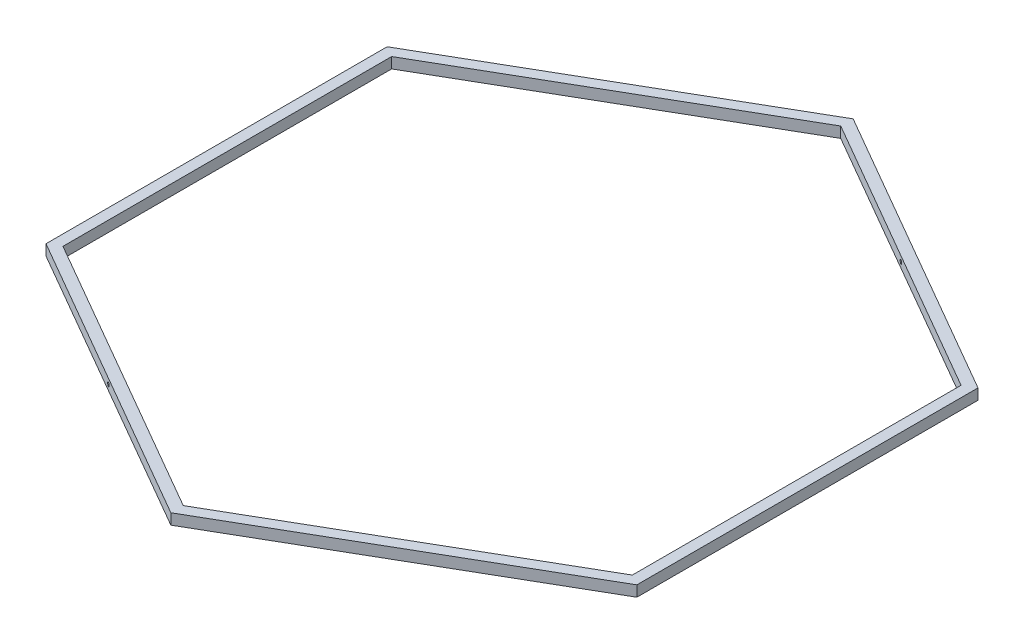
SolidWorks part; units mm, degrees
ref_plane "Plano frontal" through (0, 0, 0) normal (0, 0, 1) x (1, 0, 0)
ref_plane "Plano superior" through (0, 0, 0) normal (0, 1, 0) x (1, 0, 0)
ref_plane "Plano direito" through (0, 0, 0) normal (1, 0, 0) x (0, 0, -1)
sketch "Esboço1" plane through (0, 0, 0) normal (0, 1, 0) x (1, 0, 0)
  line L0 (110, -63.5085) -> (110, 63.5085)
  line L1 (110, 63.5085) -> (0, 127.0171)
  line L2 (0, 127.0171) -> (-110, 63.5085)
  line L3 (-110, 63.5085) -> (-110, -63.5085)
  line L4 (-110, -63.5085) -> (0, -127.0171)
  line L5 (0, -127.0171) -> (110, -63.5085)
  line L6 (106, 61.1991) -> (0, 122.3983)
  line L7 (0, 122.3983) -> (-106, 61.1991)
  line L8 (-106, 61.1991) -> (-106, -61.1991)
  line L9 (-106, -61.1991) -> (0, -122.3983)
  line L10 (0, -122.3983) -> (106, -61.1991)
  line L11 (106, -61.1991) -> (106, 61.1991)
  circle A0 centre (0, 0) radius 110 construction
  dimension "D1" = 220
  dimension "D2" = 4
extrude "Ressalto-extrusão1" add sketch "Esboço1" along normal blind 4
sketch "Esboço2" plane through (-55, 0, 95.2628) normal (-0.5, 0, 0.866) x (0.866, 0, 0.5)
  line L0 (-63.5085, 2) -> (0, 2) construction
  line L1 (-63.5085, 4) -> (-63.5085, 0) construction
  line L2 (0, 2) -> (63.5085, 2) construction
  line L3 (63.5085, 4) -> (63.5085, 0) construction
  circle A0 centre (0, 2) radius 0.75
  dimension "D1" = 1.5
extrude "Corte-extrusão1" cut sketch "Esboço2" against normal through all
